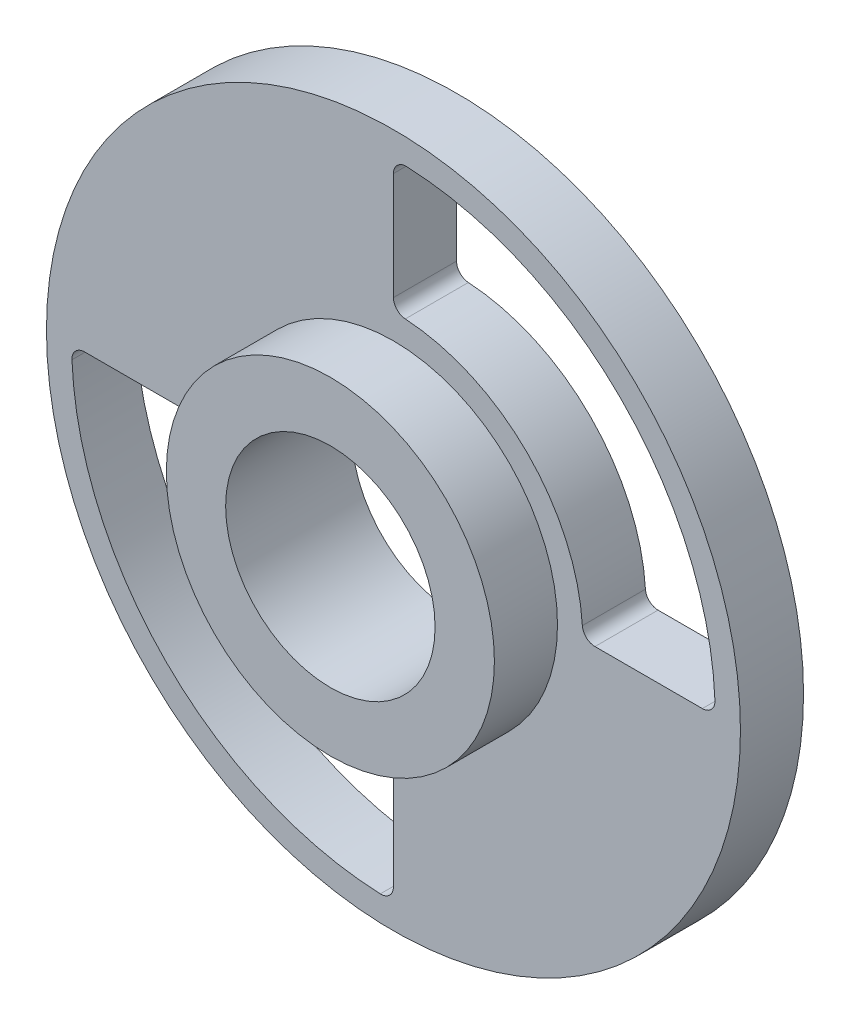
SolidWorks part; units mm, degrees
ref_plane "Front Plane" through (0, 0, 0) normal (0, 0, 1) x (1, 0, 0)
ref_plane "Top Plane" through (0, 0, 0) normal (0, 1, 0) x (1, 0, 0)
ref_plane "Right Plane" through (0, 0, 0) normal (1, 0, 0) x (0, 0, -1)
sketch "Sketch1" plane through (0, 0, 0) normal (0, 0, 1) x (1, 0, 0)
  circle A0 centre (0, 0) radius 4.15
  circle A1 centre (0, 0) radius 13.75
  dimension "D1" = 27.5
  dimension "D2" = 8.3
extrude "Boss-Extrude1" add sketch "Sketch1" along normal blind 2.5
sketch "Sketch2" plane through (0, 0, 2.5) normal (0, 0, 1) x (1, 0, 0)
  circle A0 centre (0, 0) radius 4.15
  circle A1 centre (0, 0) radius 6.5
  circle A2 centre (0, 0) radius 4.15 construction
  circle A3 centre (0, 0) radius 4 construction
  dimension "D1" = 8
  dimension "D2" = 2.5
extrude "Boss-Extrude2" add sketch "Sketch2" along normal blind 2.5
sketch "Sketch5" plane through (0, 0, 0) normal (0, 0, 1) x (1, 0, 0)
  line L0 (0, 0) -> (0, 7.5) construction
  line L1 (0, 7.5) -> (0, 12.75)
  line L2 (0, 0) -> (7.5, 0) construction
  line L3 (7.5, 0) -> (12.75, 0)
  circle A0 centre (0, 0) radius 12.75
  circle A1 centre (0, 0) radius 7.5
  circle A2 centre (0, 0) radius 13.75 construction
  circle A3 centre (0, 0) radius 6.5 construction
  dimension "D1" = 1
  dimension "D2" = 1
  dimension "D3" = 90
extrude "Cut-Extrude1" cut sketch "Sketch5" along normal through all contours A1 L3 A0 L1
fillet "Fillet1" radius 0.5 4 edges at (7.5, 0, 1.25) (12.75, 0, 1.25) (0, 7.5, 1.25) (0, 12.75, 1.25)
pattern_circular "CirPattern1" count 2 over 360 about axis through (0, 0, 0) along (0, 0, 1) of "Cut-Extrude1", "Fillet1"
